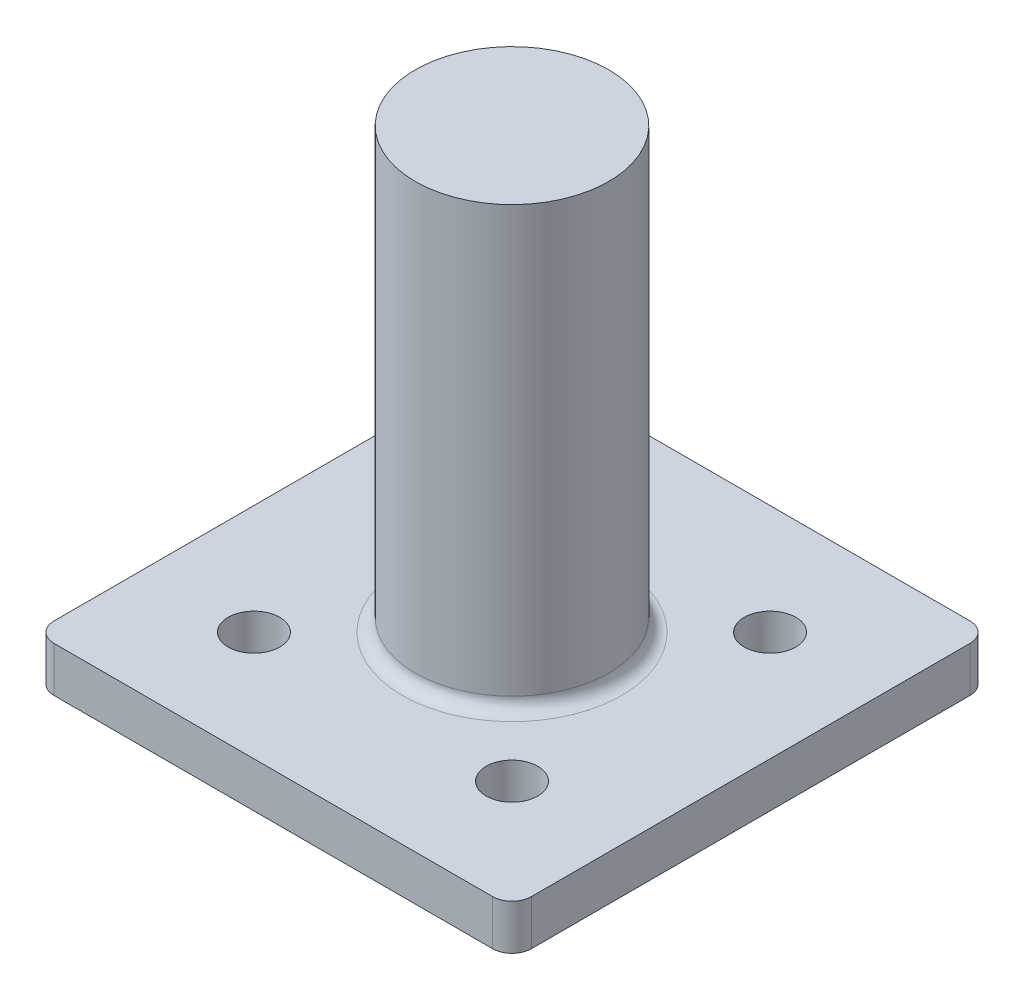
SolidWorks part; units mm, degrees
material "Stainless Steel (ferritic)"
ref_plane "Front" through (0, 0, 0) normal (0, 0, 1) x (1, 0, 0)
ref_plane "Top" through (0, 0, 0) normal (0, 1, 0) x (1, 0, 0)
ref_plane "Right" through (0, 0, 0) normal (1, 0, 0) x (0, 0, -1)
sketch "Sketch1" plane through (0, 0, 0) normal (0, 1, 0) x (1, 0, 0)
  line L0 (3, 0) -> (71, 0)
  line L1 (74, 3) -> (74, 71)
  line L2 (71, 74) -> (3, 74)
  line L3 (0, 71) -> (0, 3)
  arc A0 (0, 3) -> (3, 0) centre (3, 3) ccw
  arc A1 (74, 3) -> (71, 0) centre (71, 3) cw
  arc A2 (74, 71) -> (71, 74) centre (71, 71) ccw
  arc A3 (3, 74) -> (0, 71) centre (3, 71) ccw
  point P7 (0, 0)
  point P10 (74, 0)
  point P13 (74, 74)
  dimension "D3" = 3
  dimension "D1" = 74
  dimension "D2" = 74
extrude "Boss-Extrude1" add sketch "Sketch1" along normal blind 7
sketch "Sketch2" plane through (0, 7, 0) normal (0, 1, 0) x (1, 0, 0)
  line L0 (37, 74) -> (37, 0) construction
  line L1 (71, 74) -> (3, 74) construction
  line L2 (3, 0) -> (71, 0) construction
  line L3 (0, 37) -> (74, 37) construction
  line L4 (0, 71) -> (0, 3) construction
  line L5 (74, 3) -> (74, 71) construction
  circle A0 centre (37, 37) radius 15
  dimension "D1" = 30
extrude "Boss-Extrude2" add sketch "Sketch2" along normal blind 68
fillet "Fillet1" radius 2 1 edges at (37, 7, -22)
sketch "Sketch3" plane through (0, 7, 0) normal (0, 1, 0) x (1, 0, 0)
  line L0 (3, 74) -> (3, 0) construction
  line L1 (71, 74) -> (71, 0) construction
  line L2 (71, 37) -> (57, 37) construction
  line L4 (57, 37) -> (57, 17) construction
  line L5 (37, 0) -> (37, 26.4133) construction
  line L6 (3, 0) -> (71, 0) construction
  line L7 (37, 17) -> (17, 17) construction
  line L9 (37, 17) -> (57, 17) construction
  line L10 (3, 37) -> (17, 37) construction
  line L11 (17, 37) -> (17, 17) construction
  arc A0 (0, 3) -> (3, 0) centre (3, 3) ccw construction
  circle A3 centre (17, 17) radius 4
  circle A4 centre (57, 17) radius 4
  dimension "D1" = 8
  dimension "D3" = 20
  dimension "D2" = 8
  dimension "D4" = 20
  dimension "D5" = 20
  dimension "D8" = 20
sketch "Sketch4" plane through (0, 7, 0) normal (0, 1, 0) x (1, 0, 0)
  line L0 (0, 37) -> (71, 37) construction
  line L1 (0, 71) -> (0, 3) construction
  line L2 (71, 74) -> (71, 0) construction
ref_plane "Plane1" through (0, 0, -37) normal (0, 0, 1) x (1, 0, 0)
extrude "Cut-Extrude1" cut sketch "Sketch3" against normal blind 10
mirror "Mirror1" about plane through (0, 0, -37) normal (0, 0, 1) of "Cut-Extrude1"
